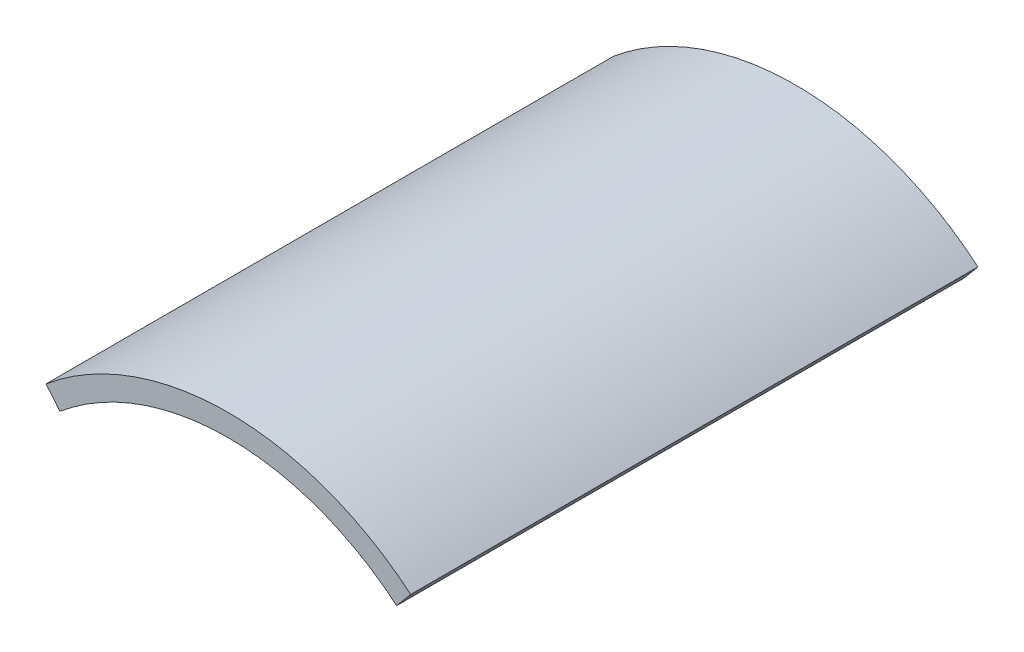
SolidWorks part; units mm, degrees
material "Custom Plastic"
ref_plane "Front Plane" through (0, 0, 0) normal (0, 0, 1) x (1, 0, 0)
ref_plane "Top Plane" through (0, 0, 0) normal (0, 1, 0) x (1, 0, 0)
ref_plane "Right Plane" through (0, 0, 0) normal (1, 0, 0) x (0, 0, -1)
sketch "Sketch1" plane through (0, 0, 0) normal (0, 0, 1) x (1, 0, 0)
  line L0 (-32.1394, 38.3022) -> (0, 0) construction
  line L1 (0, 0) -> (0, 50) construction
  line L2 (32.1394, 38.3022) -> (0, 0) construction
  line L3 (38.5673, 45.9627) -> (25.7115, 30.6418)
  line L4 (-38.5673, 45.9627) -> (-25.7115, 30.6418)
  line L5 (-32.1394, 38.3022) -> (0, 65.2704) construction
  line L6 (-32.1394, 38.3022) -> (0, 38.3022) construction
  arc A0 (32.1394, 38.3022) -> (-32.1394, 38.3022) centre (0, 0) ccw construction
  arc A1 (38.5673, 45.9627) -> (-38.5673, 45.9627) centre (0, 0) ccw
  arc A2 (25.7115, 30.6418) -> (-25.7115, 30.6418) centre (0, 0) ccw
  dimension "D1" = 100
  dimension "D2" = 40
  dimension "D3" = 10
  dimension "D4" = 10
extrude "Boss-Extrude1" add sketch "Sketch1" along normal mid plane 20
ref_plane "Plane1" through (0, 0, 0) normal (-1, 0, 0) x (0, 0, 1)
sketch "Sketch3" plane through (0, 0, 10) normal (0, 0, 1) x (1, 0, 0)
  line L0 (-41.7812, 49.7929) -> (-38.5673, 45.9627)
  line L1 (41.7812, 49.7929) -> (38.5673, 45.9627)
  arc A1 (38.5673, 45.9627) -> (-38.5673, 45.9627) centre (0, 0) ccw construction
  arc A2 (41.7812, 49.7929) -> (-41.7812, 49.7929) centre (0, 0) ccw
  arc A3 (41.7812, 49.7929) -> (-41.7812, 49.7929) centre (0, 0) ccw
  arc A4 (38.5673, 45.9627) -> (-38.5673, 45.9627) centre (0, 0) ccw
  dimension "D1" = 5
extrude "Boss-Extrude2" add sketch "Sketch3" along normal blind 130 separate body
sketch "Sketch4" plane through (0, 0, 10) normal (0, 0, 1) x (1, 0, 0)
  line L2 (-38.5673, 45.9627) -> (-25.7115, 30.6418)
  line L3 (25.7115, 30.6418) -> (38.5673, 45.9627)
  line L4 (-38.5673, 45.9627) -> (-25.7115, 30.6418)
  line L5 (25.7115, 30.6418) -> (38.5673, 45.9627)
  arc A2 (38.5673, 45.9627) -> (-38.5673, 45.9627) centre (0, 0) ccw
  arc A3 (25.7115, 30.6418) -> (-25.7115, 30.6418) centre (0, 0) ccw
  arc A4 (38.5673, 45.9627) -> (-38.5673, 45.9627) centre (0, 0) ccw
  arc A5 (25.7115, 30.6418) -> (-25.7115, 30.6418) centre (0, 0) ccw
  dimension "D1" = 0
extrude "Cut-Extrude1" cut sketch "Sketch4" against normal blind 130
